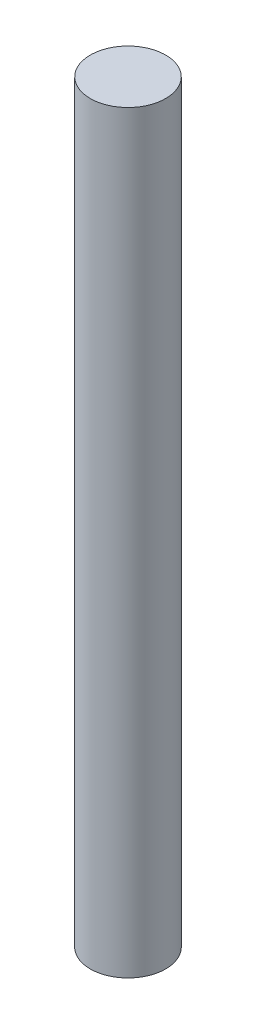
SolidWorks part; units mm, degrees
ref_plane "Front" through (0, 0, 0) normal (0, 0, 1) x (1, 0, 0)
ref_plane "Top" through (0, 0, 0) normal (0, 1, 0) x (1, 0, 0)
ref_plane "Right" through (0, 0, 0) normal (1, 0, 0) x (0, 0, -1)
sketch "Skizze1" plane through (0, 0, 0) normal (0, 1, 0) x (1, 0, 0)
  circle A0 centre (0, 0) radius 15
  dimension "D1" = 30
extrude "Aufsatz-Linear austragen1" add sketch "Skizze1" along normal blind 300
